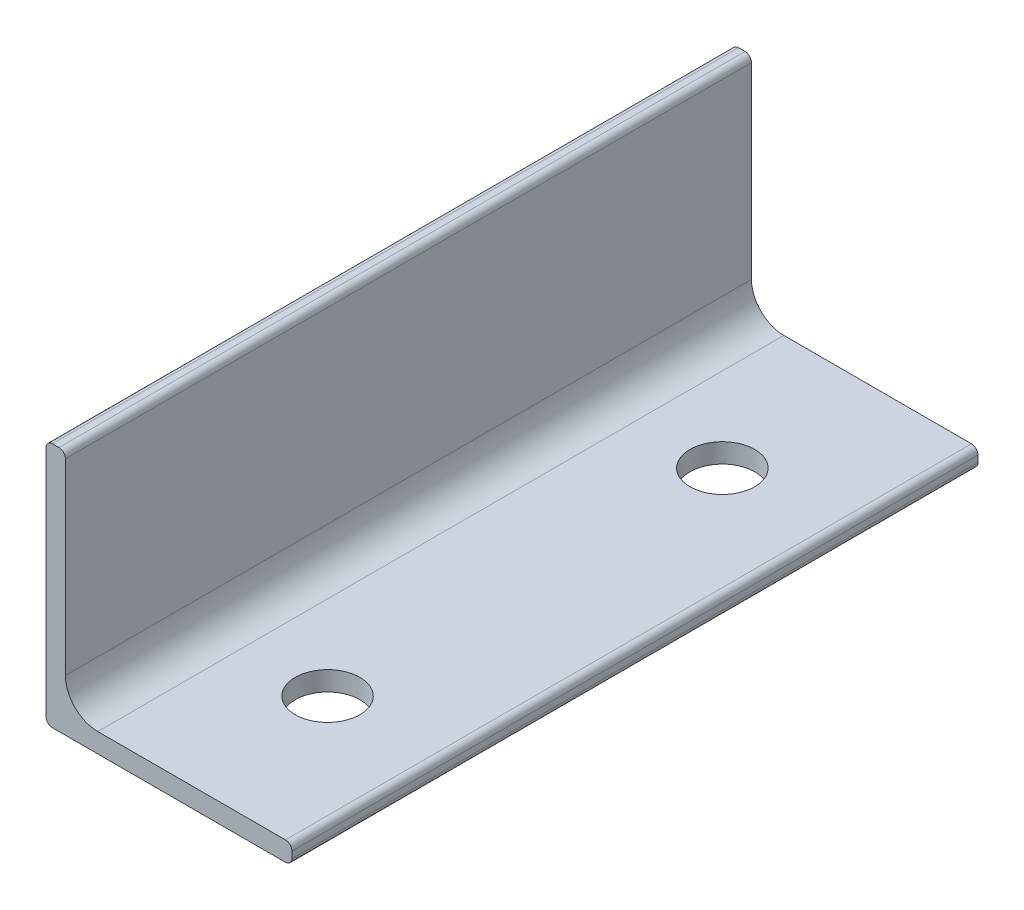
SolidWorks part; units mm, degrees
material "Q235锻制"
ref_plane "前视基准面" through (0, 0, 0) normal (0, 0, 1) x (1, 0, 0)
ref_plane "上视基准面" through (0, 0, 0) normal (0, 1, 0) x (1, 0, 0)
ref_plane "右视基准面" through (0, 0, 0) normal (1, 0, 0) x (0, 0, -1)
sketch "草图1" plane through (0, 0, 0) normal (0, 0, 1) x (1, 0, 0)
  line L0 (0, 1) -> (0, 37)
  line L1 (0, -55) -> (0, 55) construction
  line L2 (1, 38) -> (2, 38)
  line L3 (3, 37) -> (3, 8)
  line L4 (8, 3) -> (37, 3)
  line L5 (38, 2) -> (38, 1)
  line L6 (55, 0) -> (-55, 0) construction
  line L7 (37, 0) -> (1, 0)
  arc A0 (3, 8) -> (8, 3) centre (8, 8) ccw
  arc A1 (38, 1) -> (37, 0) centre (37, 1) cw
  arc A2 (37, 3) -> (38, 2) centre (37, 2) cw
  arc A3 (2, 38) -> (3, 37) centre (2, 37) cw
  arc A4 (0, 37) -> (1, 38) centre (1, 37) cw
  arc A5 (0, 1) -> (1, 0) centre (1, 1) ccw
  point P15 (38, 0)
  point P18 (38, 3)
  point P21 (3, 38)
  point P24 (0, 38)
  point P27 (0, 0)
  dimension "D5" = 5
  dimension "D6" = 1
  dimension "D1" = 38
  dimension "D2" = 38
  dimension "D3" = 3
  dimension "D4" = 3
extrude "凸台-拉伸1" add sketch "草图1" along normal mid plane 106
sketch "草图3" plane through (0, 3, 0) normal (0, 1, 0) x (1, 0, 0)
  line L0 (21, -30.5) -> (21, 30.5) construction
  line L2 (-20.9, 0) -> (20.9, 0) construction
  line L3 (38, -53) -> (38, 53) construction
  circle A0 centre (21, 30.5) radius 5
  circle A1 centre (21, -30.5) radius 5
  point P3 (21, 0)
  dimension "D3" = 10
  dimension "D4" = 10
  dimension "D1" = 61
  dimension "D2" = 17
extrude "切除-拉伸1" cut sketch "草图3" against normal through all
